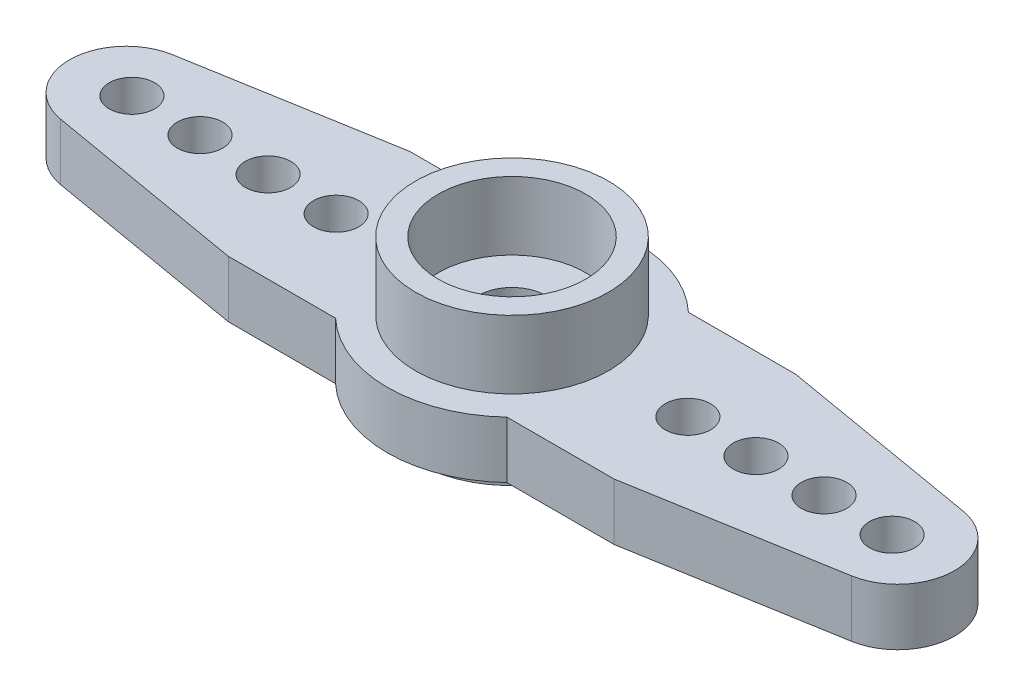
SolidWorks part; units mm, degrees
ref_plane "Front Plane" through (0, 0, 0) normal (0, 0, 1) x (1, 0, 0)
ref_plane "Top Plane" through (0, 0, 0) normal (0, 1, 0) x (1, 0, 0)
ref_plane "Right Plane" through (0, 0, 0) normal (1, 0, 0) x (0, 0, -1)
sketch "Sketch1" plane through (0, 0, 0) normal (0, 1, 0) x (1, 0, 0)
  line L0 (-19.5, 0) -> (19.5, 0) construction
  line L1 (-8.5, -4) -> (8.5, -4)
  line L2 (-8.5, -4) -> (-8.5, 4) construction
  line L3 (-8.5, 4) -> (8.5, 4)
  line L4 (8.5, -4) -> (8.5, 4) construction
  line L5 (0, 4) -> (0, -4) construction
  line L6 (-8.5, 0) -> (8.5, 0) construction
  line L7 (-8.5, 4) -> (-17.4241, 2.4638)
  line L8 (-8.5, -4) -> (-17.4241, -2.4638)
  line L9 (8.5, -4) -> (17.4241, -2.4638)
  line L10 (8.5, 4) -> (17.4241, 2.4638)
  arc A0 (3.7749, 4) -> (-3.7749, 4) centre (0, 0) ccw
  circle A1 centre (0, 0) radius 1.5
  arc A2 (-17.4241, 2.4638) -> (-17.4241, -2.4638) centre (-17, 0) ccw
  arc A3 (17.4241, 2.4638) -> (17.4241, -2.4638) centre (17, 0) cw
  arc A4 (-3.7749, -4) -> (3.7749, -4) centre (0, 0) ccw
  circle A5 centre (7.75, 0) radius 1
  circle A6 centre (10.75, 0) radius 1
  circle A7 centre (13.75, 0) radius 1
  circle A8 centre (16.75, 0) radius 1
  circle A9 centre (-16.75, 0) radius 1
  circle A10 centre (-13.75, 0) radius 1
  circle A11 centre (-7.75, 0) radius 1
  circle A12 centre (-10.75, 0) radius 1
  point P10 (0, 0)
  point P22 (6.75, 0)
  dimension "D1" = 11
  dimension "D2" = 3
  dimension "D6" = 5
  dimension "D7" = 6.75
  dimension "D8" = 2
  dimension "D9" = 4
  dimension "D10" = 3
  dimension "D3" = 8
  dimension "D4" = 17
  dimension "D5" = 39
extrude "Boss-Extrude1" add sketch "Sketch1" along normal mid plane 2.5 contours A3 L10 L3 L7 A2 L8 L1 L9 A11 A9 A8 A7 A6 A5 A1 A10 A12 | L3 A0 | L1 A4
sketch "Sketch3" plane through (0, 0, 0) normal (0, 1, 0) x (1, 0, 0)
  circle A0 centre (0, 0) radius 4.25
  circle A1 centre (0, 0) radius 3.25
  dimension "D1" = 8.5
  dimension "D2" = 6.5
extrude "Boss-Extrude2" add sketch "Sketch3" along normal blind 3 and the other way blind 3.5 from surface at 1.25 starting at face at (-7.75, 1.25, 1)
